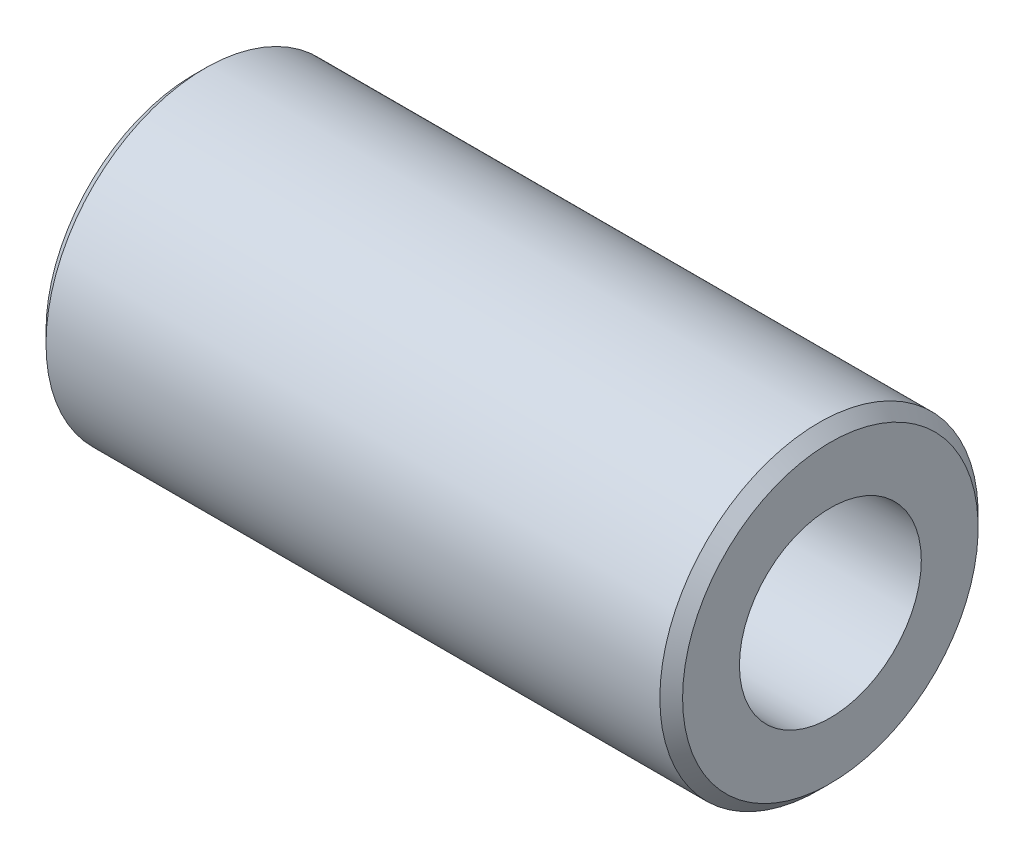
SolidWorks part; units mm, degrees
ref_plane "Front" through (0, 0, 0) normal (0, 0, 1) x (1, 0, 0)
ref_plane "Top" through (0, 0, 0) normal (0, 1, 0) x (1, 0, 0)
ref_plane "Right" through (0, 0, 0) normal (1, 0, 0) x (0, 0, -1)
sketch "草图1" plane through (0, 0, 0) normal (0, 0, 1) x (1, 0, 0)
  line L0 (18.1256, 0) -> (-18.1256, 0)
  line L1 (-14, 7) -> (14, 7)
  line L2 (-14, 7) -> (-14, 4)
  line L3 (-14, 4) -> (14, 4)
  line L4 (14, 7) -> (14, 4)
  line L5 (-14, 7) -> (14, 4) construction
  line L6 (-14, 4) -> (14, 7) construction
  point P0 (0, 5.5)
  point P5 (0, 4)
  point P10 (0, 0)
  dimension "D1" = 4
  dimension "D2" = 28
  dimension "D3" = 7
revolve "旋转1" add sketch "草图1" angle 360 about L0
chamfer "倒角1" distance 0.5 angle 45 2 edges at (14, 0, -7) (-14, 0, -7)
